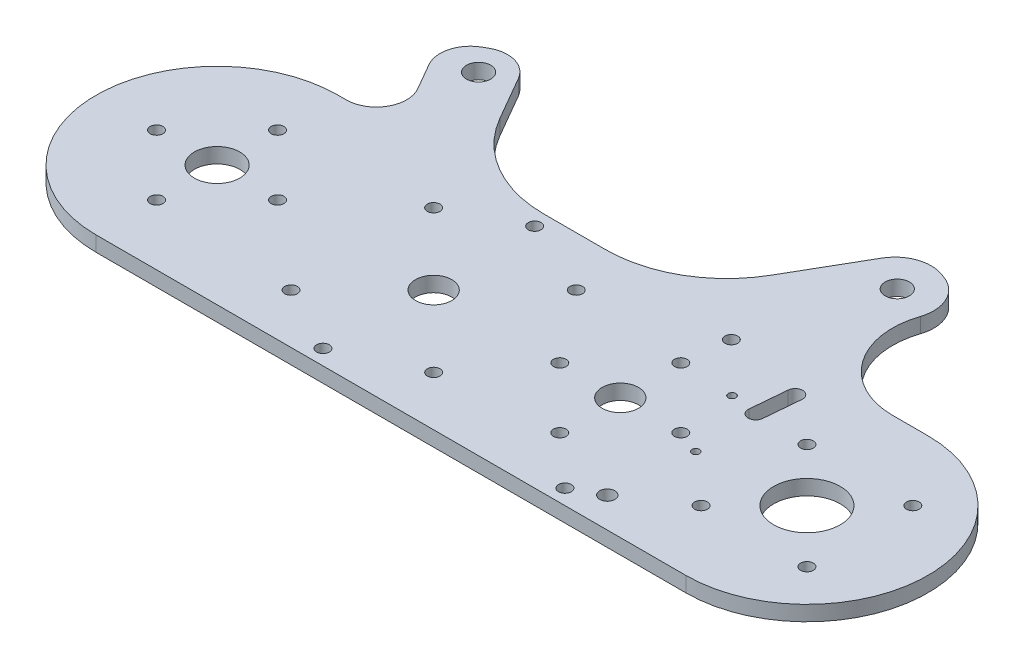
SolidWorks part; units mm, degrees
material "6061 Alloy"
ref_plane "Front Plane" through (0, 0, 0) normal (0, 0, 1) x (1, 0, 0)
ref_plane "Top Plane" through (0, 0, 0) normal (0, 1, 0) x (1, 0, 0)
ref_plane "Right Plane" through (0, 0, 0) normal (1, 0, 0) x (0, 0, -1)
sketch "Sketch1" plane through (0, 0, 0) normal (0, 1, 0) x (1, 0, 0)
  line L0 (-97.5, 0) -> (97.5, 0) construction
  line L1 (-97.5, 40) -> (97.5, 40)
  line L2 (-97.5, -40) -> (97.5, -40)
  line L3 (-27.5, 35) -> (37.5, 35) construction
  line L4 (-2.75, 0) -> (2.75, 0) construction
  line L5 (80, -17.5) -> (115, -17.5)
  line L6 (80, -17.5) -> (80, 17.5)
  line L7 (115, -17.5) -> (115, 17.5)
  line L8 (80, 17.5) -> (115, 17.5)
  line L9 (80, -17.5) -> (115, 17.5) construction
  line L10 (115, -17.5) -> (80, 17.5) construction
  arc A0 (-97.5, 40) -> (-97.5, -40) centre (-97.5, 0) ccw
  arc A1 (97.5, -40) -> (97.5, 40) centre (97.5, 0) ccw
  circle A2 centre (97.5, 0) radius 11
  circle A3 centre (-97.5, 0) radius 11
  circle A4 centre (35.8, 0) radius 6
  circle A5 centre (-97.5, 0) radius 7.5
  circle A6 centre (-97.5, 0) radius 20
  circle A7 centre (-97.5, 0) radius 20
  circle A8 centre (-97.5, -20) radius 2.1
  circle A9 centre (-117.5, 0) radius 2.1
  circle A10 centre (-97.5, 20) radius 2.1
  circle A11 centre (-77.5, 0) radius 2.1
  circle A12 centre (-25.9, 0) radius 6
  circle A13 centre (-27.5, 35) radius 2.1
  circle A14 centre (37.5, 35) radius 2.1
  circle A15 centre (52.5, -35) radius 2.1
  circle A16 centre (-27.5, -35) radius 2.1
  circle A17 centre (115, 17.5) radius 2.1
  circle A18 centre (115, -17.5) radius 2.1
  circle A19 centre (80, -17.5) radius 2.1
  circle A20 centre (80, 17.5) radius 2.1
  circle A21 centre (97.5, 0) radius 22 construction
  circle A22 centre (35.8, 0) radius 20 construction
  circle A23 centre (55.8, 0) radius 2.1
  circle A24 centre (35.8, -20) radius 2.1
  circle A25 centre (15.8, 0) radius 2.1
  circle A26 centre (35.8, 20) radius 2.1
  circle A27 centre (-25.9, 0) radius 37.1149 construction
  circle A28 centre (-2.33, -23.57) radius 2.1
  circle A32 centre (-49.47, -23.57) radius 2.1
  circle A33 centre (-49.47, 23.57) radius 2.1
  circle A34 centre (-2.33, 23.57) radius 2.1
  circle A36 centre (61.5, -30) radius 2.5
  circle A38 centre (53.6439, 19.0883) radius 1.25
  circle A39 centre (63.6439, -2.9117) radius 1.25
  point P2 (0, 0)
  point P27 (-95, 0)
  point P61 (35.8, 0)
  point P72 (-25.9, 0)
  point P73 (-25.9, 12.1917)
  dimension "D2" = 40
  dimension "D3" = 22
  dimension "D4" = 22
  dimension "D5" = 12
  dimension "D7" = 40
  dimension "D8" = 15
  dimension "D9" = 4.2
  dimension "D10" = 40
  dimension "D11" = 12
  dimension "D13" = 65
  dimension "D14" = 4.2
  dimension "D18" = 44
  dimension "D17" = 4.2
  dimension "D20" = 4.2
  dimension "D22" = 40
  dimension "D23" = 4.2
  dimension "D24" = 23.57
  dimension "D27" = 35
  dimension "D29" = 2.5
  dimension "D30" = 80
  dimension "D1" = 195
  dimension "D6" = 61.7
  dimension "D12" = 61.7
  dimension "D15" = 5
  dimension "D16" = 70
  dimension "D21" = 23.57
  dimension "D25" = 23.57
  dimension "D28" = 35
  dimension "D19" = 4
  dimension "D26" = 4
extrude "Boss-Extrude1" add sketch "Sketch1" along normal blind 5
sketch "Sketch3" plane through (0, 0, 0) normal (0, 1, 0) x (1, 0, 0)
  line L0 (-97.5, -40) -> (97.5, -40) construction
  line L1 (-65.7839, -30) -> (3.2173, -30)
  line L2 (-65.7839, -30) -> (-65.7839, 50)
  line L3 (-65.7839, 50) -> (3.2173, 50)
  line L4 (3.2173, -30) -> (3.2173, 50)
  line L5 (-65.7839, -30) -> (3.2173, 50) construction
  line L6 (-65.7839, 50) -> (3.2173, -30) construction
  line L7 (-74.409, 60) -> (11.8424, 60)
  line L8 (-74.409, 60) -> (-74.409, -40)
  line L9 (-74.409, -40) -> (11.8424, -40)
  line L10 (11.8424, 60) -> (11.8424, -40)
  line L11 (-74.409, 60) -> (11.8424, -40) construction
  line L12 (-74.409, -40) -> (11.8424, 60) construction
  line L13 (-97.5, 40) -> (97.5, 40) construction
  point P0 (-31.2833, 10)
  point P5 (-31.2833, 10)
  dimension "D1" = 80
  dimension "D2" = 10
sketch "Sketch4" plane through (0, 5, 0) normal (0, 1, 0) x (1, 0, 0)
  line L0 (-52.5, 40) -> (-77.5, 83.3013)
  line L1 (-97.5, 40) -> (97.5, 40) construction
  line L2 (-77.5, 83.3013) -> (-96.25, 72.476)
  line L3 (-96.25, 72.476) -> (-77.5, 40)
  line L4 (-77.5, 40) -> (-52.5, 40)
  circle A0 centre (-80.8577, 69.8157) radius 4
  dimension "D4" = 10
  dimension "D5" = 12
  dimension "D6" = 8
  dimension "D1" = 20
  dimension "D2" = 25
  dimension "D3" = 50
  dimension "D7" = 120
extrude "Boss-Extrude2" add sketch "Sketch4" against normal blind 5
fillet "Fillet1" radius 40 1 edges at (-52.5, 2.5, -40)
fillet "Fillet2" radius 10 3 edges at (-77.5, 2.5, -40) (-96.25, 2.5, -72.476) (-77.5, 2.5, -83.3013)
sketch "Sketch6" plane through (0, 5, 0) normal (0, 1, 0) x (1, 0, 0)
  line L2 (65.2446, 17.6099) -> (66.2905, 29.5642) construction
  line L3 (65.2446, 17.6099) -> (66.2905, 29.5642)
  line L4 (60.2636, 18.0457) -> (61.3095, 30)
  arc A2 (60.2636, 18.0457) -> (65.2446, 17.6099) centre (62.7541, 17.8278) ccw construction
  arc A3 (66.2905, 29.5642) -> (61.3095, 30) centre (63.8, 29.7821) ccw construction
  arc A4 (60.2636, 18.0457) -> (65.2446, 17.6099) centre (62.7541, 17.8278) ccw
  arc A5 (66.2905, 29.5642) -> (61.3095, 30) centre (63.8, 29.7821) ccw
extrude "Cut-Extrude2" cut sketch "Sketch6" against normal through all
sketch "Sketch7" plane through (0, 5, 0) normal (0, 1, 0) x (1, 0, 0)
  line L0 (42.5, 40) -> (67.5, 83.3013)
  line L1 (-29.406, 40) -> (97.5, 40) construction
  line L2 (67.5, 83.3013) -> (44.0479, 91.9615)
  line L3 (44.0479, 91.9615) -> (14.0479, 40)
  circle A0 centre (50.3988, 76.9615) radius 4
  line M40 (97.5, 40) -> (-29.406, 40)
  dimension "D6" = 15
  dimension "D7" = 13
  dimension "D8" = 8
  dimension "D1" = 120
  dimension "D2" = 25
  dimension "D3" = 50
  dimension "D4" = 60
  dimension "D5" = 55
extrude "Boss-Extrude3" add sketch "Sketch7" against normal blind 5 contours L2 L3 L0 A0 M40
fillet "Fillet3" radius 25 1 edges at (42.5, 2.5, -40)
fillet "Fillet4" radius 12 2 edges at (44.0479, 2.5, -91.9615) (67.5, 2.5, -83.3013)
fillet "Fillet5" radius 40 1 edges at (14.0479, 2.5, -40)
